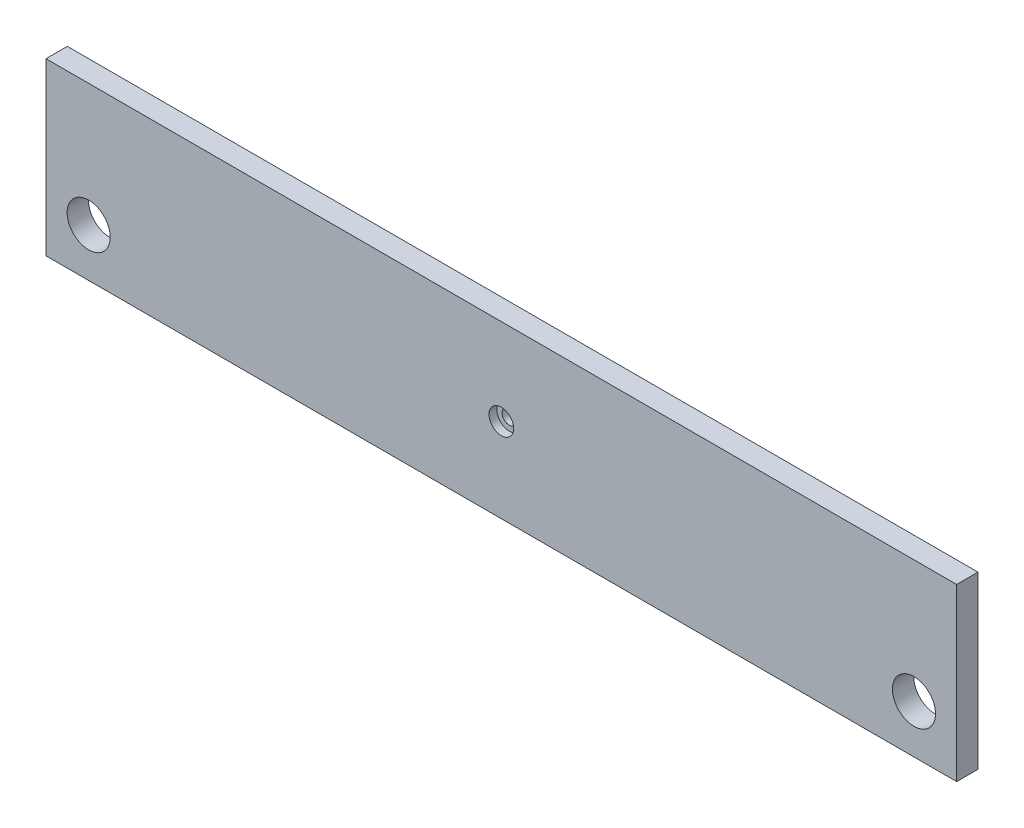
SolidWorks part; units mm, degrees
material "Pine"
ref_plane "Front Plane" through (0, 0, 0) normal (0, 0, 1) x (1, 0, 0)
ref_plane "Top Plane" through (0, 0, 0) normal (0, 1, 0) x (1, 0, 0)
ref_plane "Right Plane" through (0, 0, 0) normal (1, 0, 0) x (0, 0, -1)
sketch "Sketch1" plane through (0, 0, 0) normal (0, 0, 1) x (1, 0, 0)
  line L1 (0, 0) -> (812.8, 0)
  line L2 (0, 0) -> (0, 152.4)
  line L3 (0, 152.4) -> (812.8, 152.4)
  line L4 (812.8, 0) -> (812.8, 152.4)
  dimension "D1" = 812.8
  dimension "D2" = 152.4
extrude "Boss-Extrude1" add sketch "Sketch1" along normal blind 19.05
sketch "Sketch2" plane through (0, 0, 19.05) normal (0, 0, 1) x (1, 0, 0)
  line L0 (38.1, 42.926) -> (774.7, 42.926) construction
  line L1 (774.7, 42.926) -> (812.8, 42.926) construction
  line L2 (812.8, 152.4) -> (0, 152.4) construction
  line L3 (812.8, 0) -> (812.8, 152.4) construction
  line L4 (38.1, 42.926) -> (0, 42.926) construction
  line L6 (0, 152.4) -> (0, 0) construction
  circle A0 centre (38.1, 42.926) radius 19.2405
  circle A1 centre (774.7, 42.926) radius 19.2405
  dimension "D1" = 38.481
  dimension "D2" = 38.1
  dimension "D3" = 109.474
extrude "Cut-Extrude1" cut sketch "Sketch2" against normal blind 19.05
sketch "Sketch3" plane through (0, 0, 19.05) normal (0, 0, 1) x (1, 0, 0)
  line L0 (406.4, 42.926) -> (406.4, 75.2094) construction
  line L3 (38.1, 42.926) -> (774.7, 42.926) construction
  circle A0 centre (406.4, 75.2094) radius 10.9982
  point P2 (406.4, 42.926)
  dimension "D1" = 21.9964
  dimension "D3" = 32.2834
extrude "Cut-Extrude2" cut sketch "Sketch3" against normal blind 6.985
sketch "Sketch4" plane through (0, 0, 12.065) normal (0, 0, 1) x (1, 0, 0)
  circle A0 centre (406.4, 75.2094) radius 6.35
  circle A2 centre (406.4, 75.2094) radius 10.9982 construction
  dimension "D1" = 12.7
extrude "Cut-Extrude3" cut sketch "Sketch4" against normal through all
sketch "Sketch5" plane through (0, 0, 19.05) normal (0, 0, 1) x (1, 0, 0)
  line L1 (382.8288, 98.7806) -> (429.9712, 51.6382) construction
  line L2 (382.8288, 51.6382) -> (429.9712, 51.6382) construction
  line L3 (382.8288, 51.6382) -> (382.8288, 98.7806) construction
  line L4 (382.8288, 98.7806) -> (429.9712, 98.7806) construction
  line L5 (429.9712, 51.6382) -> (429.9712, 98.7806) construction
  circle A0 centre (406.4, 75.2094) radius 15.875
  circle A1 centre (382.8288, 98.7806) radius 2.5
  circle A2 centre (429.9712, 98.7806) radius 2.5
  circle A3 centre (429.9712, 51.6382) radius 2.5
  circle A4 centre (382.8288, 51.6382) radius 2.5
  point P11 (406.4, 75.2094)
  dimension "D1" = 31.75
  dimension "D3" = 5
  dimension "D2" = 47.1424
extrude "Cut-Extrude4" [suppressed] cut sketch "Sketch5" against normal through all
